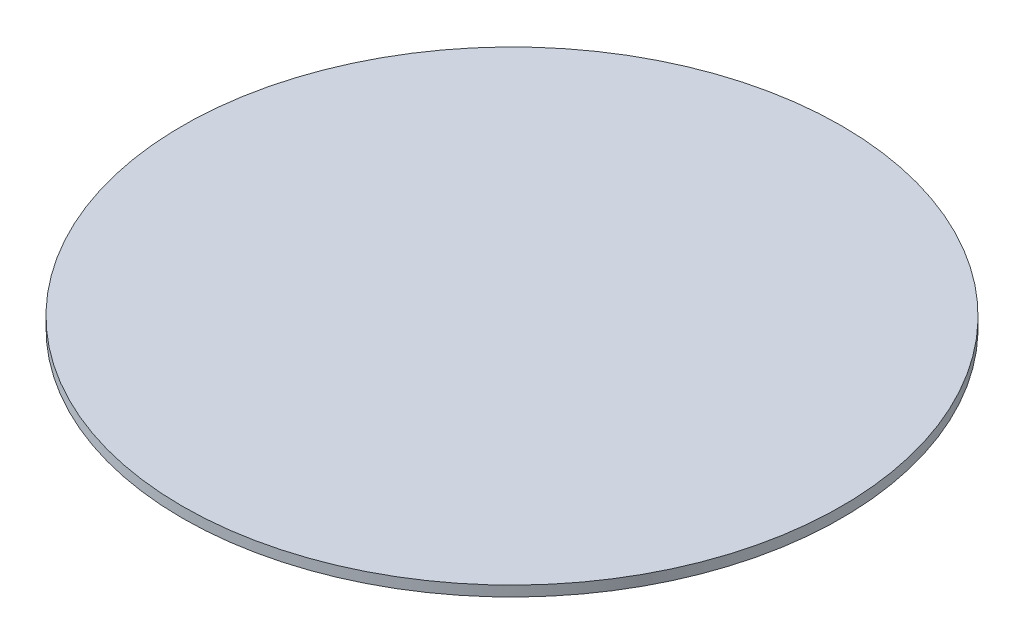
SolidWorks part; units mm, degrees
ref_plane "Plano frontal" through (0, 0, 0) normal (0, 0, 1) x (1, 0, 0)
ref_plane "Plano superior" through (0, 0, 0) normal (0, 1, 0) x (1, 0, 0)
ref_plane "Plano direito" through (0, 0, 0) normal (1, 0, 0) x (0, 0, -1)
sketch "Esboço1" plane through (0, 0, 0) normal (0, 1, 0) x (1, 0, 0)
  circle A0 centre (0, 0) radius 47.8
  dimension "D1" = 95.6
extrude "Ressalto-extrusão1" add sketch "Esboço1" along normal blind 1.5
